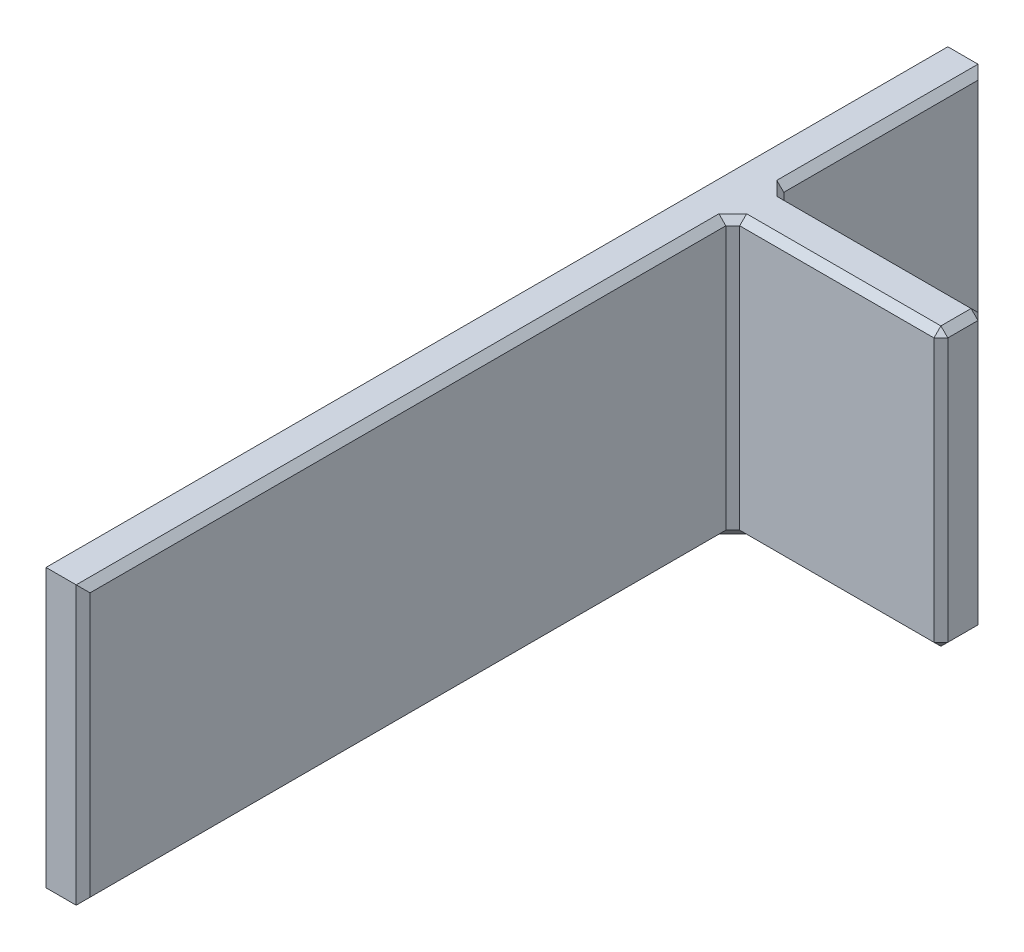
SolidWorks part; units mm, degrees
ref_plane "Alzado" through (0, 0, 0) normal (0, 0, 1) x (1, 0, 0)
ref_plane "Planta" through (0, 0, 0) normal (0, 1, 0) x (1, 0, 0)
ref_plane "Vista lateral" through (0, 0, 0) normal (1, 0, 0) x (0, 0, -1)
sketch "Croquis1" plane through (0, 0, 0) normal (0, 0, 1) x (1, 0, 0)
  line L1 (3.175, -20) -> (-3.175, -20)
  line L2 (3.175, -20) -> (3.175, 20)
  line L3 (3.175, 20) -> (-3.175, 20)
  line L4 (-3.175, -20) -> (-3.175, 20)
  line L5 (3.175, -20) -> (-3.175, 20) construction
  line L6 (3.175, 20) -> (-3.175, -20) construction
  point P0 (0, 0)
  dimension "D1" = 6.35
  dimension "D2" = 40
extrude "Saliente-Extruir1" add sketch "Croquis1" along normal blind 130
sketch "Croquis2" plane through (3.175, 0, 0) normal (1, 0, 0) x (0, 0, -1)
  line L0 (0, 0) -> (-30, 0) construction
  line L1 (-30, 20) -> (-30, -20)
  line L2 (-130, 20) -> (0, 20) construction
  line L3 (-130, -20) -> (0, -20) construction
  line L4 (-30, -20) -> (-36.35, -20)
  line L5 (-36.35, -20) -> (-36.35, 20)
  line L6 (-36.35, 20) -> (-30, 20)
  dimension "D1" = 30
  dimension "D2" = 6.35
extrude "Saliente-Extruir2" add sketch "Croquis2" along normal blind 30
chamfer "Chaflán1" distance 1 angle 45 20 edges at (18.175, 20, 30) (18.175, -20, 30) (3.175, 20, 15) (3.175, 0, 0) (3.175, -20, 15) (3.175, 0, 30) (33.175, 0, 30) (33.175, -20, 33.175) (33.175, 0, 36.35) (33.175, 20, 33.175) (18.175, -20, 36.35) (18.175, 20, 36.35) (3.175, -20, 83.175) (3.175, 0, 130) (3.175, 20, 83.175) (3.175, 0, 36.35) (-3.175, 20, 65) (-3.175, 0, 130) (-3.175, -20, 65) (-3.175, 0, 0)
